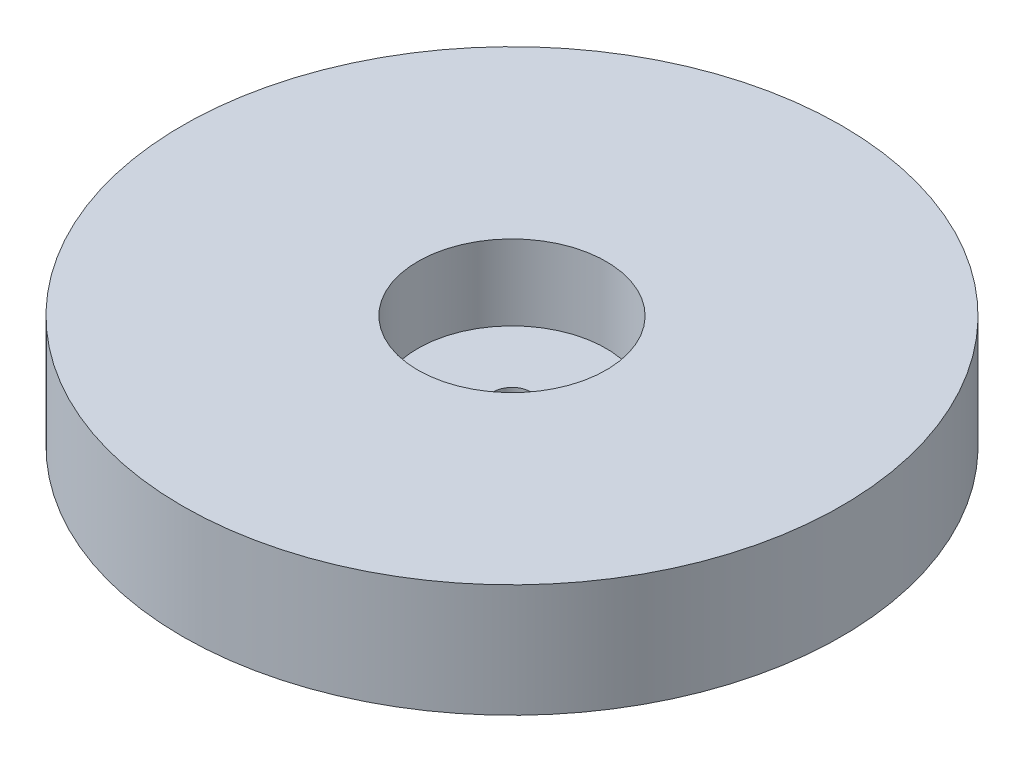
SolidWorks part; units mm, degrees
ref_plane "Plan de face" through (0, 0, 0) normal (0, 0, 1) x (1, 0, 0)
ref_plane "Plan de dessus" through (0, 0, 0) normal (0, 1, 0) x (1, 0, 0)
ref_plane "Plan de droite" through (0, 0, 0) normal (1, 0, 0) x (0, 0, -1)
sketch "Esquisse1" plane through (0, 0, 0) normal (0, 1, 0) x (1, 0, 0)
  circle A0 centre (0, 0) radius 35
extrude "Boss.-Extru.1" add sketch "Esquisse1" along normal blind 12
sketch "Esquisse2" plane through (0, 12, 0) normal (0, 1, 0) x (1, 0, 0)
  circle A0 centre (0, 0) radius 10
extrude "Enlèv. mat.-Extru.1" cut sketch "Esquisse2" against normal blind 8
sketch "Esquisse3" plane through (0, 4, 0) normal (0, 1, 0) x (1, 0, 0)
  circle A0 centre (0, 0) radius 2
extrude "Enlèv. mat.-Extru.2" cut sketch "Esquisse3" against normal blind 8
